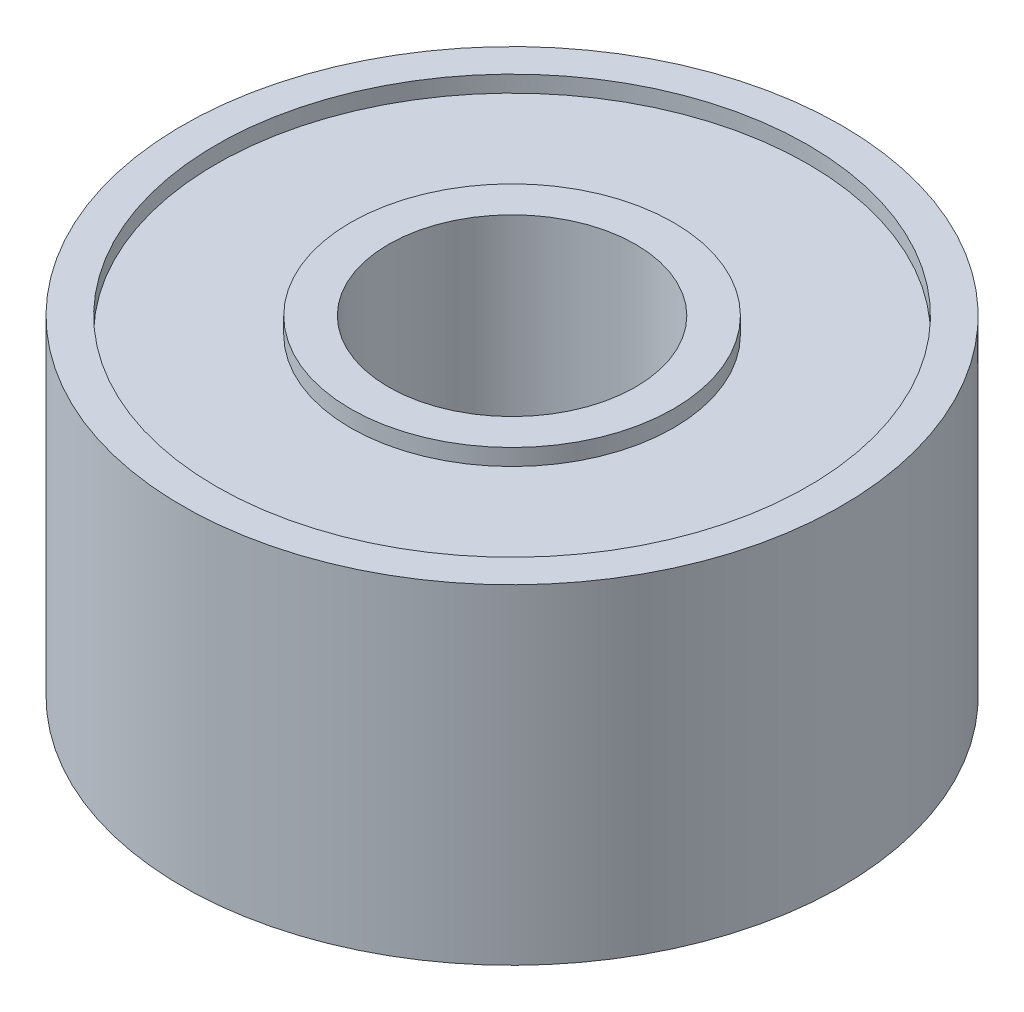
SolidWorks part; units mm, degrees
ref_plane "前视基准面" through (0, 0, 0) normal (0, 0, 1) x (1, 0, 0)
ref_plane "上视基准面" through (0, 0, 0) normal (0, 1, 0) x (1, 0, 0)
ref_plane "右视基准面" through (0, 0, 0) normal (1, 0, 0) x (0, 0, -1)
sketch "草图1" plane through (0, 0, 0) normal (0, 1, 0) x (1, 0, 0)
  circle A0 centre (0, 0) radius 1.5
  circle A1 centre (0, 0) radius 4
extrude "凸台-拉伸1" add sketch "草图1" along normal blind 4
sketch "草图2" plane through (0, 4, 0) normal (0, 1, 0) x (1, 0, 0)
  circle A0 centre (0, 0) radius 1.9597
  circle A1 centre (0, 0) radius 3.5909
extrude "切除-拉伸1" cut sketch "草图2" against normal blind 0.2
sketch "草图3" plane through (0, 0, 0) normal (0, -1, 0) x (1, 0, 0)
  circle A0 centre (0, 0) radius 1.9434
  circle A1 centre (0, 0) radius 3.5909
  circle A2 centre (0, 0) radius 3.5909
  dimension "D1" = 0
extrude "切除-拉伸2" cut sketch "草图3" against normal blind 0.2
